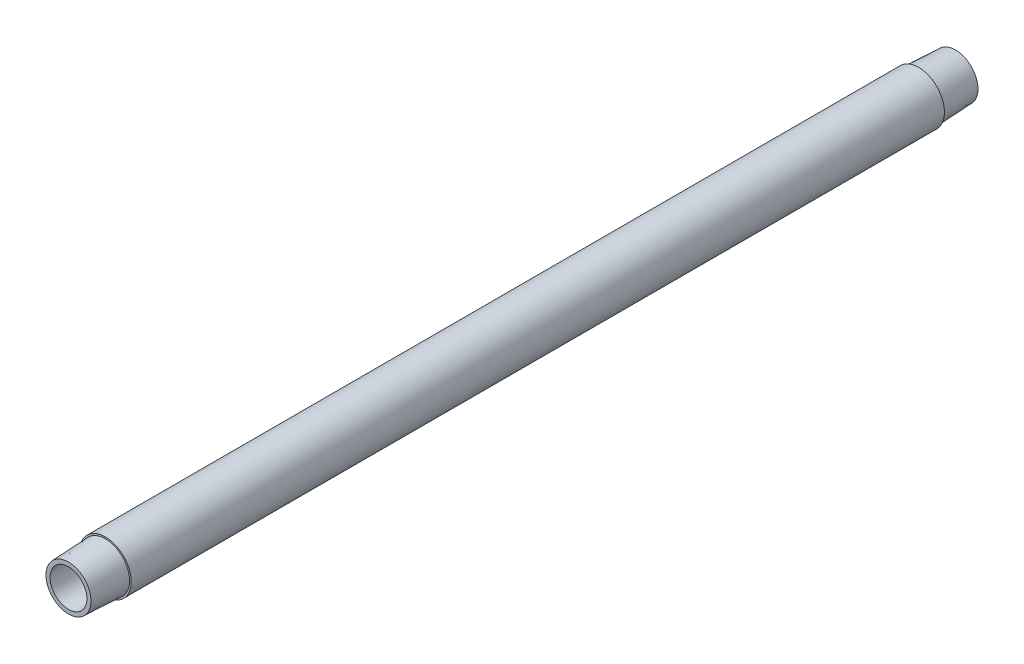
SolidWorks part; units mm, degrees
ref_plane "Front Plane" through (0, 0, 0) normal (0, 0, 1) x (1, 0, 0)
ref_plane "Top Plane" through (0, 0, 0) normal (0, 1, 0) x (1, 0, 0)
ref_plane "Right Plane" through (0, 0, 0) normal (1, 0, 0) x (0, 0, -1)
sketch "Sketch1" plane through (0, 0, 0) normal (0, 0, 1) x (1, 0, 0)
  circle A0 centre (0, 0) radius 9.525
  circle A1 centre (0, 0) radius 13.335
extrude "Boss-Extrude1" add sketch "Sketch1" along normal blind 457.2
sketch "Sketch2" plane through (0, 0, 0) normal (1, 0, 0) x (0, 0, -1)
  line L0 (0, 19.582) -> (0, 11.6045)
  line L1 (0, 11.6045) -> (-19.0074, 12.4872)
  line L2 (-19.0074, 12.4872) -> (-19.0074, 19.582)
  line L3 (-19.0074, 19.582) -> (0, 19.582)
  line L4 (-457.2, 0) -> (0, 0) construction
  line L5 (-228.6, 0) -> (-228.6, 79.6905) construction
  line L6 (-438.1926, 19.582) -> (-457.2, 19.582)
  line L7 (-438.1926, 12.4872) -> (-438.1926, 19.582)
  line L8 (-457.2, 11.6045) -> (-438.1926, 12.4872)
  line L9 (-457.2, 19.582) -> (-457.2, 11.6045)
revolve "Cut-Revolve1" cut sketch "Sketch2" angle 360 about L4
